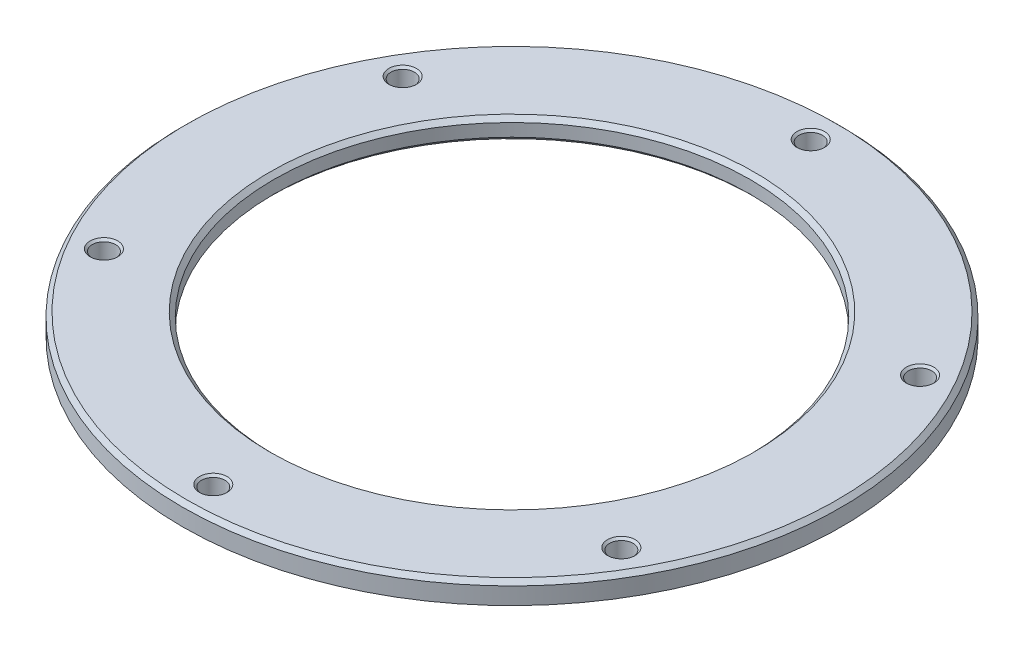
SolidWorks part; units mm, degrees
material "1023 Carbon Steel Sheet (SS)"
ref_plane "Front Plane" through (0, 0, 0) normal (0, 0, 1) x (1, 0, 0)
ref_plane "Top Plane" through (0, 0, 0) normal (0, 1, 0) x (1, 0, 0)
ref_plane "Right Plane" through (0, 0, 0) normal (1, 0, 0) x (0, 0, -1)
sketch "Sketch1" plane through (0, 0, 0) normal (0, 1, 0) x (1, 0, 0)
  circle A0 centre (0, 0) radius 77.5
  circle A1 centre (0, 0) radius 56
  dimension "D1" = 155
  dimension "D2" = 112
extrude "Boss-Extrude1" add sketch "Sketch1" along normal blind 5
sketch "Sketch2" plane through (0, 5, 0) normal (0, 1, 0) x (1, 0, 0)
  circle A0 centre (0, 70.25) radius 2.75
  dimension "D1" = 5.5
  dimension "D2" = 70.25
extrude "Cut-Extrude2" cut sketch "Sketch2" against normal through all contours A0
chamfer "Chamfer1" distance 0.5 angle 45 2 edges at (0, 5, -67.5) (0, 0, -67.5)
pattern_circular "CirPattern1" count 6 over 360 about axis through (0, 0, 0) along (0, 1, 0) of "Cut-Extrude2", "Chamfer1"
chamfer "Chamfer2" distance 1 angle 45 3 edges at (0, 5, 77.5) (0, 0, 56) (0, 5, 56)
